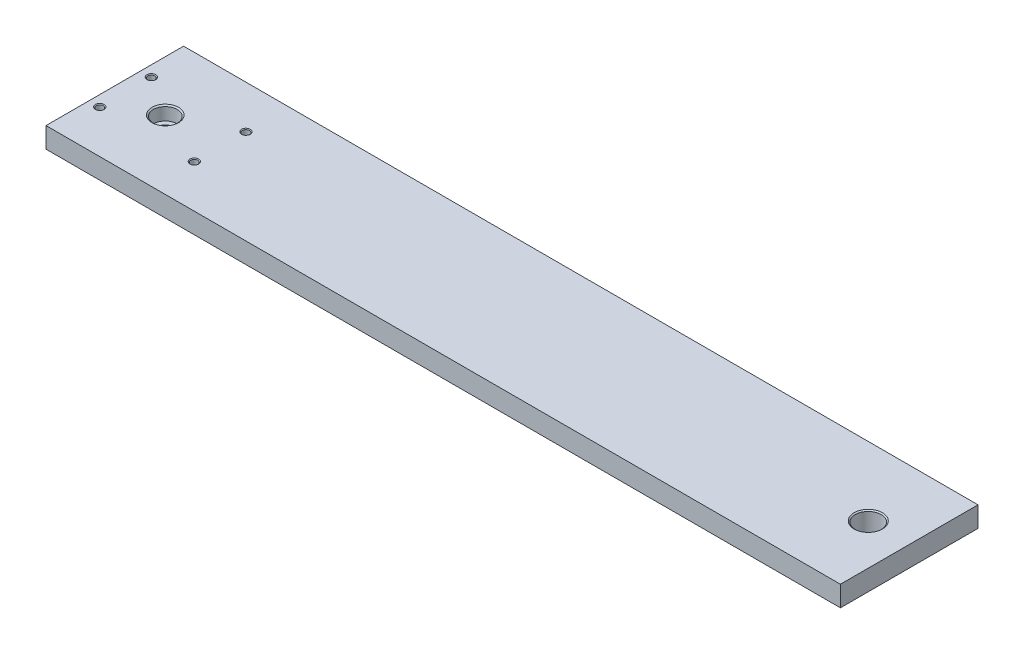
SolidWorks part; units mm, degrees
material "6061 Alloy"
ref_plane "Front" through (0, 0, 0) normal (0, 0, 1) x (1, 0, 0)
ref_plane "Top" through (0, 0, 0) normal (0, 1, 0) x (1, 0, 0)
ref_plane "Right" through (0, 0, 0) normal (1, 0, 0) x (0, 0, -1)
sketch "Sketch1" plane through (0, 0, 0) normal (0, 1, 0) x (1, 0, 0)
  line L1 (0, 0) -> (369.5738, 0)
  line L2 (0, 0) -> (0, 64)
  line L3 (0, 64) -> (369.5738, 64)
  line L4 (369.5738, 0) -> (369.5738, 64)
  dimension "D1" = 64
  dimension "D2" = 369.5738
extrude "Boss-Extrude1" add sketch "Sketch1" along normal blind 9.525
hole_wizard "15/32 (0.475) Diameter Hole1" positions "Sketch6" profile "Sketch7" hole size "15/32" standard "ANSI Inch"
sketch "Sketch6" plane through (0, 9.525, 0) normal (0, 1, 0) x (1, 0, 0)
  line L0 (350.5238, 32) -> (369.5738, 32) construction
  line L1 (369.5738, 0) -> (369.5738, 64) construction
  point P0 (350.5238, 32)
  dimension "D1" = 19.05
sketch "Sketch7" plane through (350.5238, 9.525, -32) normal (1, 0, 0) x (0, 0, 1)
  line L0 (0, 0) -> (0, 13.7339)
  line L1 (0, 13.7339) -> (6.0325, 10.1092)
  line L2 (6.0325, 10.1092) -> (6.0325, 0.4662)
  line L3 (6.0325, 0.4662) -> (6.5881, 0)
  line L5 (6.5881, 0) -> (0, 0)
  line L6 (-6.0325, 0.4662) -> (-6.5881, 0) construction
  line L10 (0, 13.7339) -> (-6.0325, 10.1092) construction
  line L11 (0, -6.35) -> (0, 107.95) construction
  dimension "Hole Dia." = 12.065
  dimension "Hole Depth" = 10.1092
  dimension "Near C'Sink Dia." = 13.1762
  dimension "Near C'Sink Angle" = 100
  dimension "Drill Angle" = 118
hole_wizard "M4x0.7 Tapped Hole1" positions "Sketch8" profile "Sketch9" tap size "M4x0.7" standard "ANSI Metric" end condition through all
sketch "Sketch8" plane through (0, 9.525, 0) normal (0, 1, 0) x (1, 0, 0)
  line L0 (49, 44) -> (49, 64) construction
  line L1 (369.5738, 64) -> (0, 64) construction
  line L3 (49, 44) -> (49, 20) construction
  line L4 (49, 20) -> (49, 0) construction
  line L5 (0, 0) -> (369.5738, 0) construction
  line L6 (49, 0) -> (49, 32) construction
  line L7 (49, 32) -> (0, 32) construction
  line L8 (0, -50) -> (0, 50) construction
  line L10 (0, 64) -> (0, 0) construction
  point P0 (49, 44)
  point P2 (49, 20)
  point P31 (5, 44)
  point P33 (5, 20)
  dimension "D2" = 44
  dimension "D3" = 5
  dimension "D4" = 24
cosmetic thread "Hole Thread1"
cosmetic thread "Hole Thread2"
sketch "Sketch9" plane through (49, 9.525, -44) normal (1, 0, 0) x (0, 0, 1)
  line L0 (0, 0) -> (0, 9.525)
  line L1 (0, 9.525) -> (1.65, 9.525)
  line L2 (1.65, 9.525) -> (1.65, 0.3147)
  line L3 (1.65, 0.3147) -> (2.025, 0)
  line L5 (2.025, 0) -> (0, 0)
  line L6 (-1.65, 0.3147) -> (-2.025, 0) construction
  line L11 (0, -6.35) -> (0, 107.95) construction
  dimension "Thru Tap Drill Dia." = 3.3
  dimension "Thru Tap Drill Depth" = 9.525
  dimension "Near C'Sink Dia." = 4.05
  dimension "Near C'Sink Angle" = 100
cosmetic thread "Hole Thread3"
cosmetic thread "Hole Thread4"
hole_wizard "CBORE for 1/4 Socket Head Cap Screw1" positions "Sketch10" profile "Sketch11" counterbore size "1/4" standard "ANSI Inch" end condition through all
sketch "Sketch10" plane through (0, 9.525, 0) normal (0, 1, 0) x (1, 0, 0)
  line L0 (23.5, 32) -> (0, 32) construction
  line L1 (0, -50) -> (0, 50) construction
  line L3 (0, 64) -> (0, 0) construction
  point P0 (23.5, 32)
  dimension "D1" = 23.5
sketch "Sketch11" plane through (23.5, 9.525, -32) normal (1, 0, 0) x (0, 0, 1)
  line L0 (0, 0) -> (0, 9.525)
  line L1 (0, 9.525) -> (3.3782, 9.525)
  line L3 (3.3782, 9.525) -> (3.3782, 6.35)
  line L4 (5.5562, 6.35) -> (3.3782, 6.35)
  line L5 (5.5562, 6.35) -> (5.5562, 0.5328)
  line L6 (5.5562, 0.5328) -> (6.1913, 0)
  line L7 (6.1913, 0) -> (0, 0)
  line L8 (-5.5562, 0.5328) -> (-6.1913, 0) construction
  line L11 (0, -6.35) -> (0, 107.95) construction
  dimension "Thru Hole Dia." = 6.7564
  dimension "Thru Hole Depth" = 9.525
  dimension "C'Bore Dia." = 11.1125
  dimension "C'Bore Depth" = 6.35
  dimension "Near C'Sink Dia." = 12.3825
  dimension "Near C'Sink Angle" = 100
